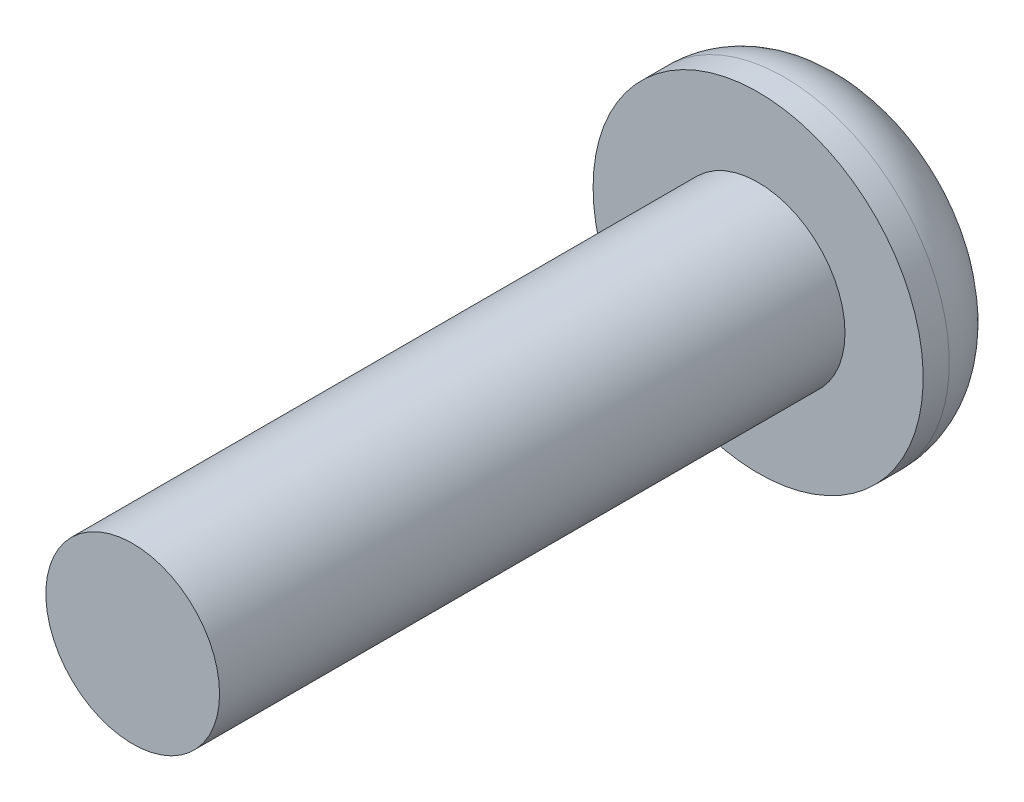
SolidWorks part; units mm, degrees
ref_plane "前视基准面" through (0, 0, 0) normal (0, 0, 1) x (1, 0, 0)
ref_plane "上视基准面" through (0, 0, 0) normal (0, 1, 0) x (1, 0, 0)
ref_plane "右视基准面" through (0, 0, 0) normal (1, 0, 0) x (0, 0, -1)
sketch "草图1" plane through (0, 0, 0) normal (0, 0, 1) x (1, 0, 0)
  circle A0 centre (0, 0) radius 2.5
extrude "凸台-拉伸1" add sketch "草图1" along normal blind 18
sketch "草图2" plane through (0, 0, 0) normal (0, 0, -1) x (-1, 0, 0)
  circle A0 centre (0, 0) radius 4.75
extrude "凸台-拉伸2" add sketch "草图2" along normal blind 2.75
fillet "圆角1" radius 2 1 edges at (-4.75, 0, -2.75)
